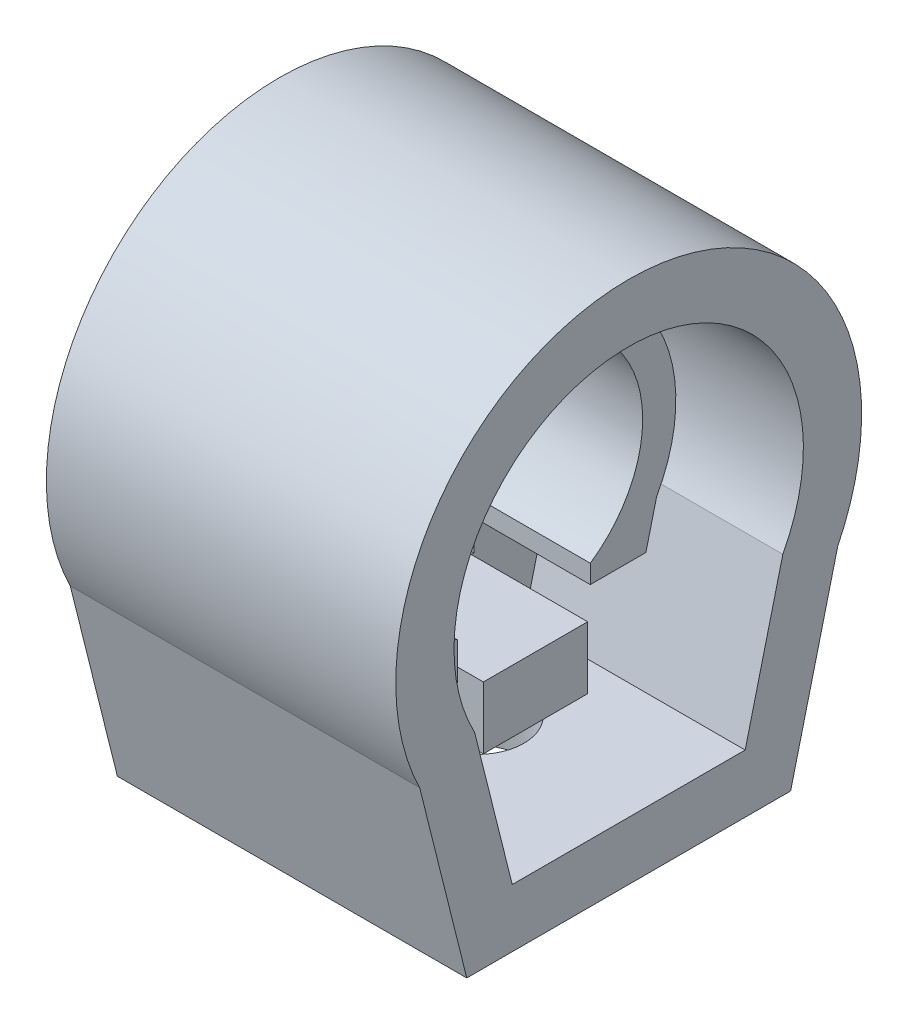
SolidWorks part; units mm, degrees
ref_plane "Alzado" through (0, 0, 0) normal (0, 0, 1) x (1, 0, 0)
ref_plane "Planta" through (0, 0, 0) normal (0, 1, 0) x (1, 0, 0)
ref_plane "Vista lateral" through (0, 0, 0) normal (1, 0, 0) x (0, 0, -1)
sketch "Croquis1" plane through (0, 0, 0) normal (1, 0, 0) x (0, 0, -1)
  line L0 (-15, 35) -> (-15, 30) construction
  line L1 (-5.7808, 0) -> (-24.2192, 0)
  line L5 (-15, 30) -> (-15, 10) construction
  line L6 (-25, 20) -> (-25, 0) construction
  line L7 (-5, 20) -> (-5, 0) construction
  line L8 (-28.2353, 12.9412) -> (-25.1894, 0.7575)
  line L9 (-1.7647, 12.9412) -> (-4.8106, 0.7575)
  line L10 (-25.1894, 0.7575) -> (-25, 0)
  line L11 (-4.8106, 0.7575) -> (-5, 0)
  line L12 (-24.2192, 0) -> (-25, 0)
  line L14 (-5.7808, 0) -> (-5, 0)
  circle A0 centre (-15, 20) radius 10
  arc A1 (-1.7647, 12.9412) -> (-28.2353, 12.9412) centre (-15, 20) ccw
  dimension "D2" = 35
  dimension "D3" = 20
  dimension "D4" = 5
extrude "Saliente-Extruir1" add sketch "Croquis1" along normal blind 11
sketch "Croquis2" plane through (11, 0, 0) normal (1, 0, 0) x (0, 0, -1)
  line L9 (-23.4775, 1.95) -> (-6.5225, 1.95)
  line L10 (-6.5225, 1.95) -> (-3.5962, 13.6552)
  line L11 (-26.4038, 13.6552) -> (-23.4775, 1.95)
  line L12 (-23.4775, 1.95) -> (-6.5225, 1.95)
  line L13 (-6.5225, 1.95) -> (-3.5962, 13.6552)
  line L14 (-26.4038, 13.6552) -> (-23.4775, 1.95)
  circle A6 centre (-15, 20) radius 10 construction
  circle A7 centre (-15, 20) radius 10
  arc A9 (-3.5962, 13.6552) -> (-26.4038, 13.6552) centre (-15, 20) ccw
  arc A10 (-3.5962, 13.6552) -> (-26.4038, 13.6552) centre (-15, 20) ccw
  dimension "D1" = 1.95
extrude "Saliente-Extruir2" add sketch "Croquis2" along normal blind 10
sketch "Croquis3" plane through (21, 0, 0) normal (1, 0, 0) x (0, 0, -1)
  line L0 (-9.5225, 1.95) -> (-9.5225, 9.95)
  line L1 (-23.4775, 1.95) -> (-6.5225, 1.95) construction
  line L2 (-9.5225, 9.95) -> (-4.5225, 9.95)
  line L3 (-6.5225, 1.95) -> (-3.5962, 13.6552) construction
  line L4 (-9.5225, 1.95) -> (-6.5225, 1.95)
  line L5 (-6.5225, 1.95) -> (-4.5225, 9.95)
  line L6 (-21.7673, 1.95) -> (-21.7673, 3.95) construction
  line L7 (-23.4775, 1.95) -> (-18.4775, 1.95)
  line L8 (-23.4775, 1.95) -> (-23.9775, 3.95)
  line L9 (-21.7673, 3.95) -> (-21.9159, 3.95) construction
  line L10 (-24.4635, 14.1403) -> (-21.5372, 2.4351)
  line L11 (-23.2421, 9.2546) -> (-21.9159, 3.95)
  line L12 (-21.9159, 3.95) -> (-23.9775, 3.95)
  line L13 (-26.4038, 13.6552) -> (-23.4775, 1.95) construction
  line L14 (-18.4775, 1.95) -> (-18.4775, 6.9452)
  line L15 (-23.2421, 9.2546) -> (-23.461, 10.1303)
  line L16 (-18.4775, 6.9452) -> (-18.4775, 7.4737)
  circle A6 centre (-15, 20) radius 13
  arc A7 (-23.461, 10.1303) -> (-18.4775, 7.4737) centre (-15, 20) ccw
  dimension "D2" = 8
  dimension "D3" = 5
  dimension "D4" = 2
  dimension "D6" = 5
  dimension "D5" = 2
  dimension "D7" = 3
extrude "Cortar-Extruir3" cut sketch "Croquis3" against normal blind 10
sketch "Croquis8" plane through (0, 1.95, 0) normal (0, -1, 0) x (1, 0, 0)
  line L1 (11, 14) -> (13.2177, 14) construction
  line L2 (11, 18.4775) -> (11, 9.5225) construction
  line L4 (14.45, 14) -> (16, 14) construction
  line L5 (16, 14) -> (17.55, 14) construction
  line L7 (17.55, 14) -> (21, 14) construction
  line L8 (21, 18.4775) -> (21, 9.5225) construction
  circle A0 centre (16, 14) radius 1.55
  dimension "D2" = 3.1
extrude "Cortar-Extruir4" cut sketch "Croquis8" against normal blind 5
sketch "Croquis10" plane through (0, 0, 0) normal (-1, 0, 0) x (0, 0, 1)
  line L4 (15, 32.3) -> (20.5, 32.3)
  line L5 (2.7, 20) -> (5, 20)
  line L6 (2.7, 20) -> (2.7, 25.5)
  line L9 (2.7, 20) -> (2.7, 14.5)
  line L10 (15, 32.3) -> (9.5, 32.3)
  line L11 (2.7, 25.5) -> (6.3506, 25.5)
  line L12 (2.7, 14.5) -> (6.3506, 14.5)
  line L13 (20.5, 32.3) -> (20.5, 28.6494)
  line L14 (9.5, 32.3) -> (9.5, 28.6494)
  line L16 (27.3, 20) -> (27.3, 14.5)
  line L17 (27.3, 20) -> (27.3, 25.5)
  line L18 (27.3, 14.5) -> (23.6494, 14.5)
  line L19 (27.3, 25.5) -> (23.6494, 25.5)
  line L21 (15, 20) -> (15, 30.25) construction
  arc A1 (9.5, 28.6494) -> (6.3506, 25.5) centre (15, 20) ccw
  arc A2 (23.6494, 25.5) -> (20.5, 28.6494) centre (15, 20) ccw
  arc A3 (6.3506, 14.5) -> (23.6494, 14.5) centre (15, 20) ccw
  circle A4 centre (15, 20) radius 10 construction
  dimension "D1" = 20.5
  dimension "D2" = 2.3
  dimension "D3" = 5.5
  dimension "D4" = 5.5
  dimension "D5" = 3
sketch "Croquis11" plane through (0, 0, 0) normal (-1, 0, 0) x (0, 0, 1)
  line L0 (15, 30.2) -> (15, 32.7) construction
  line L1 (20.7, 32.7) -> (9.3, 32.7)
  line L2 (9.3, 32.7) -> (9.3, 28.4587)
  line L3 (15, 20) -> (9.5566, 20) construction
  line L4 (20.7, 32.7) -> (20.7, 28.4587)
  line L5 (20.7, 7.3) -> (20.7, 11.5413)
  line L6 (20.7, 7.3) -> (9.3, 7.3)
  line L7 (9.3, 7.3) -> (9.3, 11.5413)
  arc A2 (20.7, 11.5413) -> (20.7, 28.4587) centre (15, 20) ccw
  arc A3 (9.3, 28.4587) -> (9.3, 11.5413) centre (15, 20) ccw
  dimension "D2" = 2.5
  dimension "D3" = 5.7
extrude "Cortar-Extruir5" cut sketch "Croquis11" against normal up to surface (21 mm away) up to face at (21, 9.5735, 16.0023)
sketch "Croquis12" plane through (21, 0, 0) normal (1, 0, 0) x (0, 0, -1)
  line L1 (-18.0021, 32.7) -> (-11.9979, 32.7)
  line L2 (-18.0021, 32.7) -> (-11.9979, 32.7)
  arc A1 (-11.9979, 32.7) -> (-18.0021, 32.7) centre (-15, 20) ccw
  arc A2 (-11.9979, 32.7) -> (-18.0021, 32.7) centre (-15, 20) ccw
  dimension "D1" = 0
extrude "Cortar-Extruir6" cut sketch "Croquis12" against normal blind 10
sketch "Croquis13" plane through (0, 0, 0) normal (-1, 0, 0) x (0, 0, 1)
  line L3 (1.0961, -5) -> (28.9039, -5)
  line L4 (28.9039, -5) -> (32.9476, 11.1748)
  line L5 (-2.9476, 11.1748) -> (1.0961, -5)
  line L6 (5, 0) -> (25, 0)
  line L7 (25, 0) -> (28.2353, 12.9412)
  line L8 (1.7647, 12.9412) -> (5, 0)
  line L9 (5, 0) -> (25, 0)
  line L10 (25, 0) -> (28.2353, 12.9412)
  line L11 (1.7647, 12.9412) -> (5, 0)
  arc A1 (32.9476, 11.1748) -> (-2.9476, 11.1748) centre (15, 20) ccw
  arc A2 (28.2353, 12.9412) -> (1.7647, 12.9412) centre (15, 20) ccw
  arc A3 (28.2353, 12.9412) -> (1.7647, 12.9412) centre (15, 20) ccw
  dimension "D1" = 0
  dimension "D2" = 5
extrude "Saliente-Extruir3" add sketch "Croquis13" against normal blind 30
sketch "Croquis14" plane through (0, -5, 0) normal (0, -1, 0) x (1, 0, 0)
  circle A0 centre (16, 14) radius 1.55 construction
  circle A1 centre (16, 14) radius 1.55 construction
  circle A2 centre (16, 14) radius 4
  dimension "D1" = 8
extrude "Cortar-Extruir7" cut sketch "Croquis14" against normal up to next
